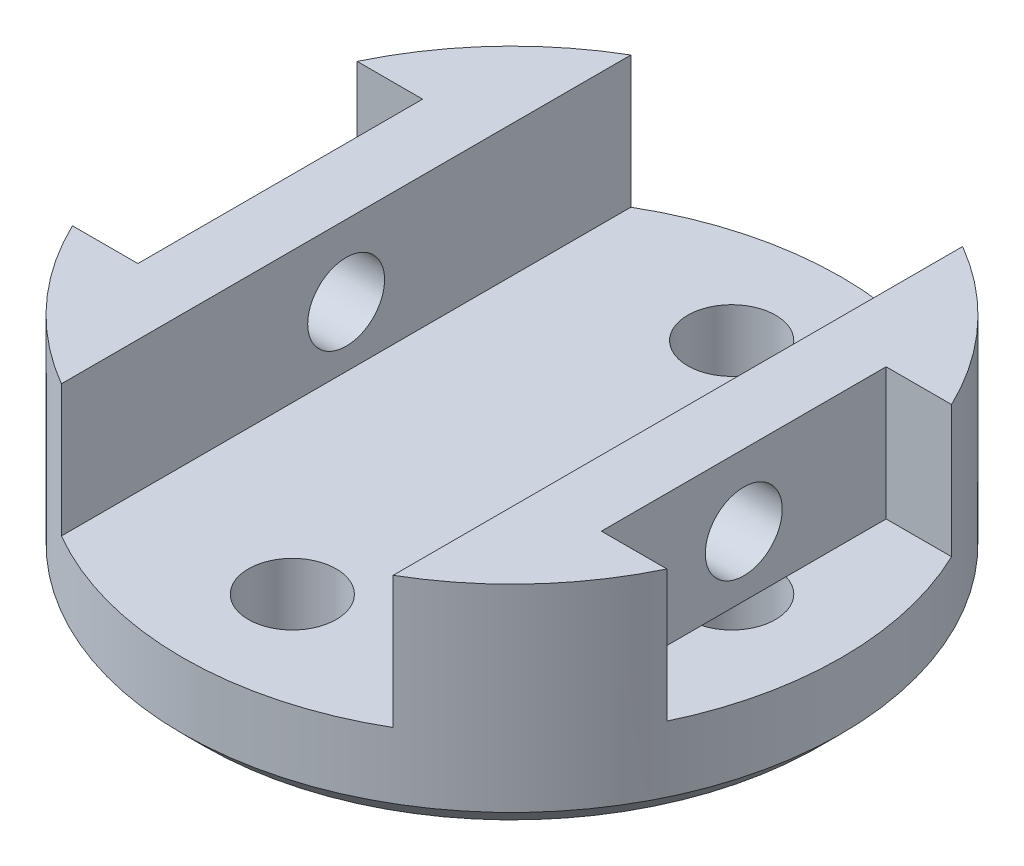
SolidWorks part; units mm, degrees
ref_plane "Front Plane" through (0, 0, 0) normal (0, 0, 1) x (1, 0, 0)
ref_plane "Top Plane" through (0, 0, 0) normal (0, 1, 0) x (1, 0, 0)
ref_plane "Right Plane" through (0, 0, 0) normal (1, 0, 0) x (0, 0, -1)
sketch "Sketch1" plane through (0, 0, 0) normal (0, 1, 0) x (1, 0, 0)
  circle A0 centre (0, 0) radius 15
  dimension "D1" = 30
extrude "Boss-Extrude1" add sketch "Sketch1" along normal blind 4
sketch "Sketch2" plane through (0, 4, 0) normal (0, 1, 0) x (1, 0, 0)
  line L0 (0, 0) -> (-10, 0) construction
  circle A0 centre (-10, 0) radius 2
  circle A1 centre (0, 10) radius 2
  circle A2 centre (10, 0) radius 2
  circle A3 centre (0, -10) radius 2
  point P13 (0, 0)
  dimension "D2" = 4
  dimension "D1" = 10
  dimension "D3" = 4
extrude "Cut-Extrude1" cut sketch "Sketch2" against normal blind 5
sketch "Sketch3" plane through (0, 0, 0) normal (0, -1, 0) x (1, 0, 0)
  circle A0 centre (-10, 0) radius 3
  circle A1 centre (0, 10) radius 3
  circle A2 centre (10, 0) radius 3
  circle A3 centre (0, -10) radius 3
  point P12 (0, 0)
  dimension "D1" = 6
  dimension "D2" = 4
sketch "Sketch4" plane through (0, 4, 0) normal (0, 1, 0) x (1, 0, 0)
  line L0 (-7.55, -16) -> (-7.55, -12.9614) construction
  line L1 (-7.55, -16) -> (7.55, -16) construction
  line L2 (-7.55, -12.9614) -> (-7.55, -0.9682)
  line L3 (-7.55, 16) -> (7.55, 16) construction
  line L4 (7.55, -12.9614) -> (7.55, -0.9682)
  line L5 (-7.55, -16) -> (7.55, 16) construction
  line L6 (-7.55, 16) -> (7.55, -16) construction
  line L7 (-7.55, 12.9614) -> (-7.55, 16) construction
  line L8 (7.55, 12.9614) -> (7.55, 16) construction
  line L9 (7.55, -16) -> (7.55, -12.9614) construction
  line L11 (-7.55, 0.9682) -> (-7.55, 12.9614)
  line L13 (7.55, 0.9682) -> (7.55, 12.9614)
  line L14 (-7.55, 0.9682) -> (-7.55, -0.9682)
  line L15 (7.55, 0.9682) -> (7.55, -0.9682)
  arc A0 (-7.55, 12.9614) -> (-7.55, -12.9614) centre (0, 0) ccw
  arc A1 (6.4012, 13.5655) -> (-6.4012, 13.5655) centre (0, 0) ccw construction
  arc A2 (-6.4012, -13.5655) -> (6.4012, -13.5655) centre (0, 0) ccw construction
  arc A3 (7.55, -12.9614) -> (7.55, 12.9614) centre (0, 0) ccw
  arc A4 (-7.55, -12.9614) -> (-6.4012, -13.5655) centre (0, 0) ccw construction
  arc A5 (-6.4012, 13.5655) -> (-7.55, 12.9614) centre (0, 0) ccw construction
  arc A6 (7.55, 12.9614) -> (6.4012, 13.5655) centre (0, 0) ccw construction
  arc A7 (6.4012, -13.5655) -> (7.55, -12.9614) centre (0, 0) ccw construction
  point P0 (0, 0)
  dimension "D3" = 30
  dimension "D1" = 32
  dimension "D2" = 15.1
extrude "Boss-Extrude3" add sketch "Sketch4" along normal blind 10
chamfer "Chamfer1" distance 1 angle 45 1 edges at (0, 0, 15)
ref_plane "Plane1" through (15, 0, 0) normal (1, 0, 0) x (0, 0, -1)
sketch "Sketch5" plane through (15, 0, 0) normal (1, 0, 0) x (0, 0, -1)
  line L0 (0, 5) -> (0, 14) construction
  line L1 (12.9614, 14) -> (-12.9614, 14) construction
  line L2 (-1.75, 6.75) -> (1.75, 6.75) construction
  circle A0 centre (0, 6.75) radius 1.75
  dimension "D1" = 3.5
  dimension "D2" = 9
extrude "Cut-Extrude2" cut sketch "Sketch5" against normal through all
sketch "Sketch7" plane through (15, 0, 0) normal (1, 0, 0) x (0, 0, -1)
  line L1 (-6.4807, 4) -> (6.4807, 4)
  line L3 (6.4807, 14) -> (-6.4807, 14)
  line L4 (0, 14) -> (0, 4) construction
  line L6 (-6.4807, 9) -> (-6.4807, 14)
  line L7 (-6.4807, 9) -> (-6.4807, 4)
  line L9 (6.4807, 9) -> (6.4807, 14)
  line L10 (6.4807, 14) -> (6.4807, 4)
  point P0 (0, 0)
  dimension "D1" = 12.9614
extrude "Cut-Extrude4" cut sketch "Sketch7" against normal offset from surface (4.45 mm away) 3 contours L4 L3 L6 L7 L1 | L3 L4 L1 L10 L9 up to face at (7.55, 6.75, -1.75)
ref_plane "Plane2" through (-15, 0, 0) normal (-1, 0, 0) x (0, 0, 1)
sketch "Sketch8" plane through (-15, 0, 0) normal (-1, 0, 0) x (0, 0, 1)
  line L1 (-6.4807, 4) -> (6.4807, 4)
  line L2 (-6.4807, 4) -> (-6.4807, 14)
  line L3 (-6.4807, 14) -> (6.4807, 14)
  line L4 (6.4807, 4) -> (6.4807, 14)
extrude "Cut-Extrude5" cut sketch "Sketch8" along direction (-1, 0, 0) on the side against the normal offset from surface (4.45 mm away) 3
sketch "Sketch9" plane through (0, 14, 0) normal (0, 1, 0) x (1, 0, 0)
  circle A0 centre (0, 0) radius 16.3422
extrude "Cut-Extrude6" cut sketch "Sketch9" against normal blind 4
